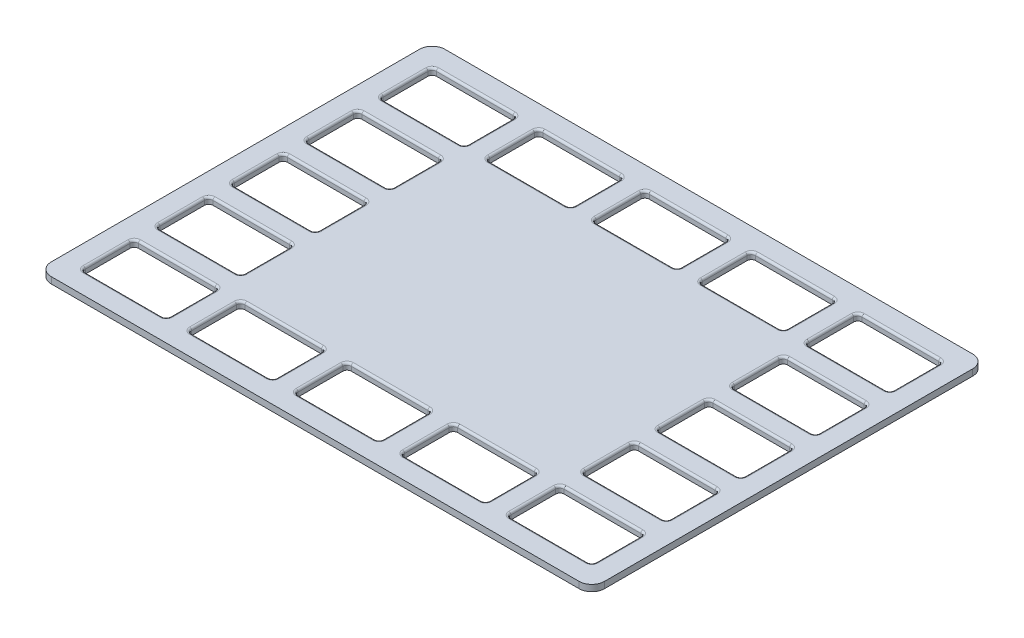
SolidWorks part; units mm, degrees
ref_plane "Front" through (0, 0, 0) normal (0, 0, 1) x (1, 0, 0)
ref_plane "Top" through (0, 0, 0) normal (0, 1, 0) x (1, 0, 0)
ref_plane "Right" through (0, 0, 0) normal (1, 0, 0) x (0, 0, -1)
sketch "Sketch1" plane through (0, 0, 0) normal (0, 1, 0) x (1, 0, 0)
  line L1 (0, 0) -> (260, 0)
  line L2 (0, 0) -> (0, 185)
  line L3 (0, 185) -> (260, 185)
  line L4 (260, 0) -> (260, 185)
  dimension "D1" = 260
  dimension "D2" = 185
extrude "Extrude1" add sketch "Sketch1" along normal blind 3
fillet "Fillet3" radius 6 4 edges at (0, 1.5, -185) (260, 1.5, -185) (260, 1.5, 0) (0, 1.5, 0)
sketch "Sketch2" plane through (0, 3, 0) normal (0, 1, 0) x (-1, 0, 0)
  line L0 (0, -179) -> (0, -6) construction
  line L1 (-10, -10) -> (-50, -10)
  line L2 (-10, -10) -> (-10, -35)
  line L3 (-10, -35) -> (-50, -35)
  line L4 (-50, -10) -> (-50, -35)
  line L5 (-6, 0) -> (-254, 0) construction
  dimension "D1" = 10
  dimension "D2" = 10
  dimension "D3" = 40
  dimension "D4" = 25
extrude "Cut-Extrude1" cut sketch "Sketch2" against normal through all
fillet "Fillet1" radius 2 4 edges at (50, 1.5, -35) (50, 1.5, -10) (10, 1.5, -10) (10, 1.5, -35)
fillet "Fillet2" radius 1 8 edges at (10.5858, 3, -10.5858) (10, 3, -22.5) (10.5858, 3, -34.4142) (30, 3, -35) (49.4142, 3, -34.4142) (50, 3, -22.5) (49.4142, 3, -10.5858) (30, 3, -10)
pattern_linear "LPattern1" count 5 spacing 50 along (1, 0, 0) count 5 spacing 35 along (0, 0, -1) skipping (1, 1), (1, 2), (1, 3), (2, 1), (2, 2), (2, 3), (3, 1), (3, 2), (3, 3) of "Cut-Extrude1", "Fillet2", "Fillet1"
